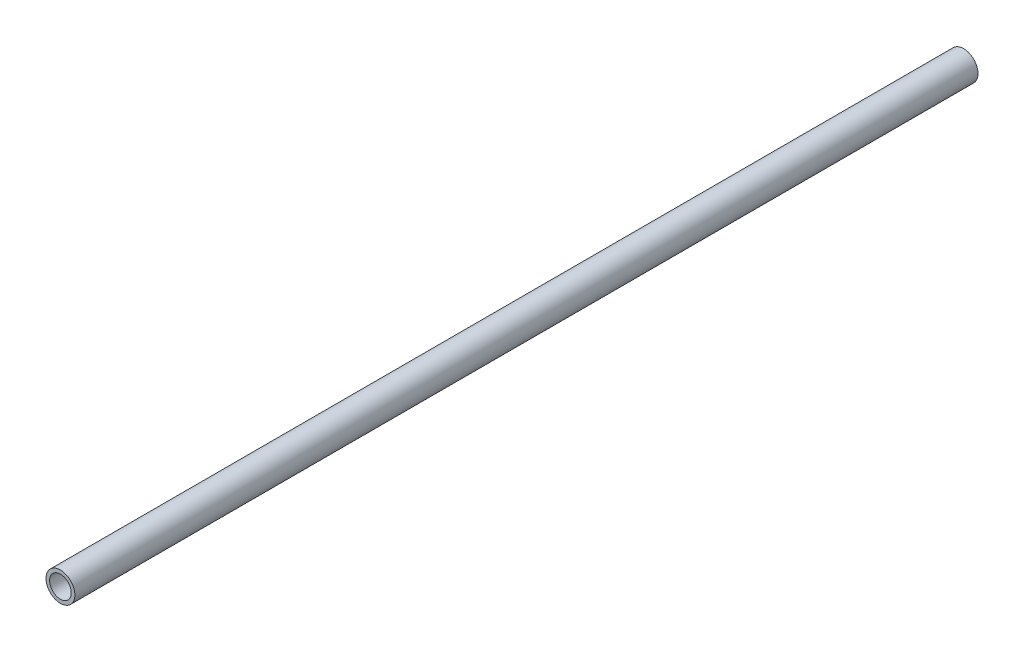
SolidWorks part; units mm, degrees
ref_plane "Front Plane" through (0, 0, 0) normal (0, 0, 1) x (1, 0, 0)
ref_plane "Top Plane" through (0, 0, 0) normal (0, 1, 0) x (1, 0, 0)
ref_plane "Right Plane" through (0, 0, 0) normal (1, 0, 0) x (0, 0, -1)
sketch "Sketch1" plane through (0, 0, 0) normal (0, 0, 1) x (1, 0, 0)
  circle A0 centre (0, 0) radius 3
  circle A1 centre (0, 0) radius 4
extrude "Boss-Extrude1" add sketch "Sketch1" along normal blind 250
